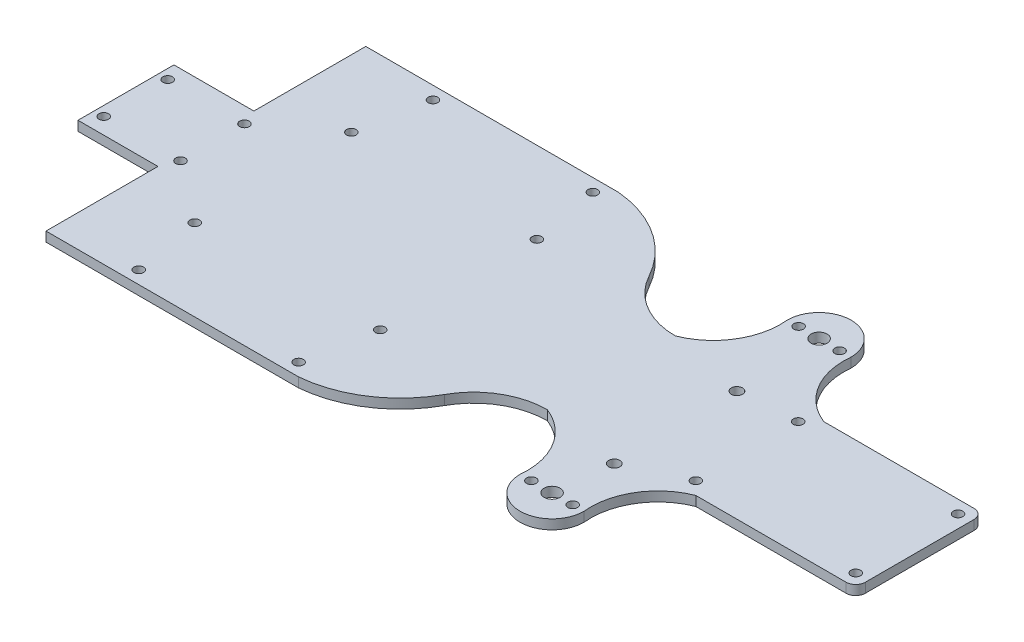
SolidWorks part; units mm, degrees
ref_plane "Alzado" through (0, 0, 0) normal (0, 0, 1) x (1, 0, 0)
ref_plane "Planta" through (0, 0, 0) normal (0, 1, 0) x (1, 0, 0)
ref_plane "Vista lateral" through (0, 0, 0) normal (1, 0, 0) x (0, 0, -1)
sketch "Croquis1" plane through (0, 0, 0) normal (0, 1, 0) x (1, 0, 0)
  line L0 (0, 0) -> (-75, 0) construction
  line L1 (-29, -24.5) -> (29, -24.5) construction
  line L2 (-29, -24.5) -> (-29, 24.5) construction
  line L3 (-29, 24.5) -> (29, 24.5) construction
  line L4 (29, -24.5) -> (29, 24.5) construction
  line L5 (-29, -24.5) -> (29, 24.5) construction
  line L6 (-29, 24.5) -> (29, -24.5) construction
  line L7 (-21, -50) -> (29, -50)
  line L8 (-75, -15) -> (-50, -15)
  line L9 (-75, -15) -> (-75, 15)
  line L10 (-75, 15) -> (-50, 15)
  line L11 (-21, 50) -> (29, 50)
  line L14 (0, 0) -> (100, 0) construction
  line L16 (100, 41.75) -> (100, -41.75) construction
  line L20 (-50, -15) -> (-50, -50)
  line L21 (-50, -50) -> (-21, -50)
  line L22 (-50, 15) -> (-50, 50)
  line L24 (123.207, 20) -> (123.207, -20) construction
  line L27 (123.207, 20) -> (76.793, -20) construction
  line L28 (123.207, -20) -> (76.793, 20) construction
  line L29 (123.207, -20) -> (170.207, -20)
  line L30 (123.207, -20) -> (123.207, 20) construction
  line L31 (123.207, 20) -> (170.207, 20)
  line L32 (173.207, -17) -> (173.207, 17)
  line L33 (-50, 50) -> (-21, 50)
  circle A0 centre (-29, 24.5) radius 1.5
  circle A1 centre (29, 24.5) radius 1.5
  circle A2 centre (29, -24.5) radius 1.5
  circle A3 centre (-29, -24.5) radius 1.5
  circle A10 centre (100, 41.75) radius 2.5
  circle A11 centre (100, -41.75) radius 2.5
  arc A14 (29, -50) -> (56.5515, -31.9803) centre (25.869, -15.1403) ccw
  arc A15 (76.793, -20) -> (56.5515, -31.9803) centre (76.793, -43.0898) ccw
  arc A16 (76.793, 20) -> (56.5515, 31.9803) centre (76.793, 43.0898) cw
  arc A17 (29, 50) -> (56.5515, 31.9803) centre (25.869, 15.1403) cw
  arc A18 (90.101, -40.3326) -> (109.899, -40.3326) centre (100, -41.75) ccw
  arc A19 (90, -41.75) -> (76.793, -20) centre (69.1104, -39.5498) ccw
  arc A20 (110, -41.75) -> (123.207, -20) centre (130.8896, -39.5498) cw
  arc A21 (90, 41.75) -> (76.793, 20) centre (69.1104, 39.5498) cw
  arc A22 (110, 41.75) -> (123.207, 20) centre (130.8896, 39.5498) ccw
  arc A23 (90.101, 40.3326) -> (109.899, 40.3326) centre (100, 41.75) cw
  arc A24 (173.207, -17) -> (170.207, -20) centre (170.207, -17) cw
  arc A25 (173.207, 17) -> (170.207, 20) centre (170.207, 17) ccw
  point P0 (0, 0)
  point P16 (-75, 0)
  point P33 (173.207, -20)
  point P37 (94.1, 2.2266)
  point P41 (178.6895, 0)
  point P45 (178.6895, 15)
  point P68 (178.6895, -15)
  dimension "D3" = 3
  dimension "D4" = 75
  dimension "D6" = 50
  dimension "D7" = 50
  dimension "D8" = 35
  dimension "D9" = 20
  dimension "D11" = 25
  dimension "D13" = 3
  dimension "D1" = 58
  dimension "D2" = 49
  dimension "D5" = 100
  dimension "D10" = 30
  dimension "D12" = 50
  dimension "D14" = 40
extrude "Saliente-Extruir1" add sketch "Croquis1" along normal blind 3
sketch "Croquis2" plane through (0, 0, 0) normal (0, -1, 0) x (1, 0, 0)
  line L0 (-75, 15) -> (-75, -15) construction
  line L1 (-48, -10.0561) -> (-72, -10.0561) construction
  line L2 (-48, -10.0561) -> (-48, 9.9439) construction
  line L3 (-48, 9.9439) -> (-72, 9.9439) construction
  line L4 (-72, -10.0561) -> (-72, 9.9439) construction
  line L5 (-48, -10.0561) -> (-72, 9.9439) construction
  line L6 (-48, 9.9439) -> (-72, -10.0561) construction
  circle A0 centre (-72, 9.9439) radius 1.5
  circle A1 centre (-48, 9.9439) radius 1.5
  circle A2 centre (-72, -10.0561) radius 1.5
  circle A3 centre (-48, -10.0561) radius 1.5
  point P0 (-60, -0.0561)
  dimension "D3" = 3
  dimension "D1" = 20
  dimension "D2" = 24
  dimension "D4" = 15
extrude "Cortar-Extruir1" cut sketch "Croquis2" against normal blind 10
sketch "Croquis4" plane through (0, 0, 0) normal (0, -1, 0) x (1, 0, 0)
  line L0 (-25, 46) -> (25, 46) construction
  line L1 (-50, 50) -> (29, 50) construction
  line L2 (-50, 15) -> (-50, 50) construction
  line L3 (119.207, 16) -> (169.207, 16) construction
  line L4 (123.207, 20) -> (170.207, 20) construction
  line L5 (173.207, 17) -> (173.207, -17) construction
  line L6 (-75, 0) -> (173.207, 0) construction
  line L7 (-75, 15) -> (-75, -15) construction
  line L8 (119.207, -16) -> (169.207, -16) construction
  line L9 (-25, -46) -> (25, -46) construction
  circle A0 centre (-25, 46) radius 1.5
  circle A1 centre (25, 46) radius 1.5
  circle A2 centre (119.207, 16) radius 1.5
  circle A3 centre (169.207, 16) radius 1.5
  circle A4 centre (169.207, -16) radius 1.5
  circle A5 centre (119.207, -16) radius 1.5
  circle A6 centre (25, -46) radius 1.5
  circle A7 centre (-25, -46) radius 1.5
  point P7 (0, 46)
  dimension "D4" = 3
  dimension "D1" = 50
  dimension "D2" = 4
  dimension "D3" = 50
  dimension "D5" = 4
  dimension "D6" = 4
  dimension "D7" = 50
extrude "Cortar-Extruir2" cut sketch "Croquis4" against normal blind 10
sketch "Croquis5" plane through (0, 0, 0) normal (0, -1, 0) x (1, 0, 0)
  line L0 (173.207, 0) -> (99.9722, 0) construction
  line L1 (173.207, 17) -> (173.207, -17) construction
  line L2 (99.9722, -16.5) -> (99.9722, 16.5) construction
  circle A0 centre (99.9722, -16.5) radius 1.5
  circle A1 centre (99.9722, 16.5) radius 1.5
  point P8 (99.9722, 0)
  dimension "D3" = 3
  dimension "D1" = 33
  dimension "D2" = 73.2348
extrude "Cortar-Extruir3" [suppressed] cut sketch "Croquis5" against normal through all
sketch "Croquis6" plane through (0, 3, 0) normal (0, 1, 0) x (1, 0, 0)
  circle A0 centre (101.8263, -24.116) radius 1.75
  arc A1 (102.4891, -18.8648) -> (101.1893, -18.8868) centre (101.8263, -18.116) ccw construction
  circle A2 centre (101.3734, 14.6802) radius 1.75
  arc A3 (100.7107, 9.429) -> (102.0105, 9.451) centre (101.3734, 8.6802) ccw construction
  dimension "D1" = 3.5
  dimension "D3" = 6
  dimension "D2" = 6
extrude "Cortar-Extruir4" cut sketch "Croquis6" against normal through all
sketch "Croquis7" plane through (0, 0, 0) normal (0, -1, 0) x (1, 0, 0)
  circle A0 centre (93.5007, -41.8474) radius 1.5
  circle A1 centre (106.4993, -41.6526) radius 1.5
  circle A2 centre (93.5001, 41.7093) radius 1.5
  circle A3 centre (106.4999, 41.7907) radius 1.5
  dimension "D1" = 3
extrude "Cortar-Extruir5" cut sketch "Croquis7" against normal blind 10
